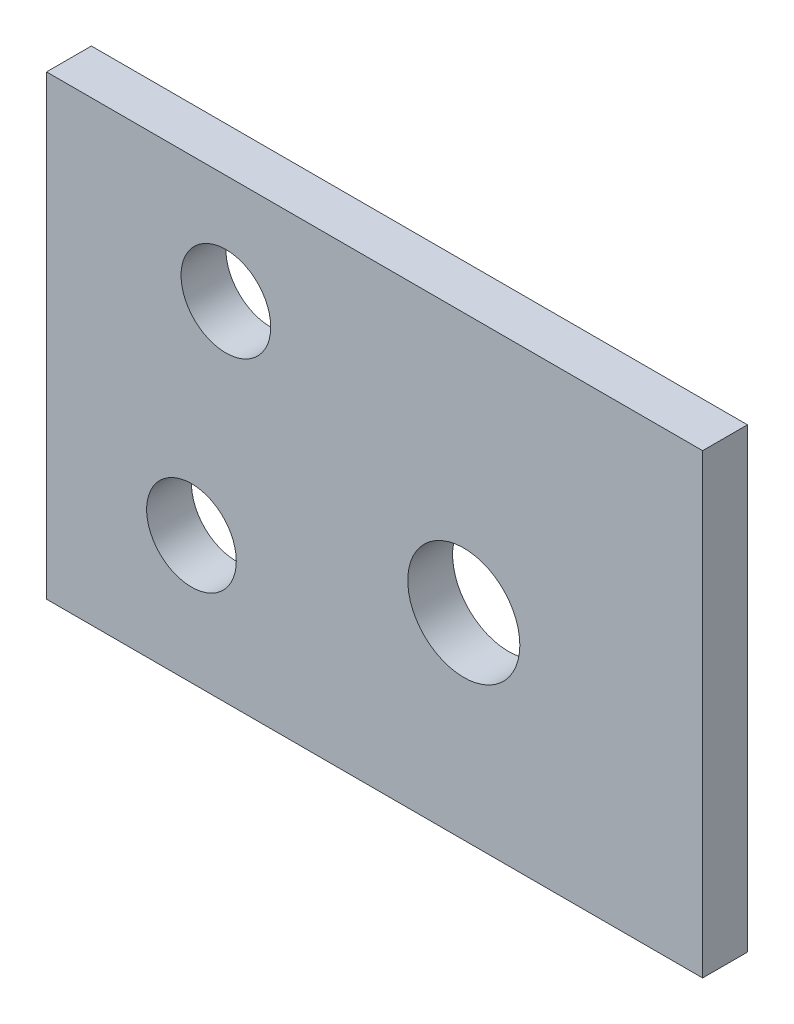
SolidWorks part; units mm, degrees
ref_plane "정면" through (0, 0, 0) normal (0, 0, 1) x (1, 0, 0)
ref_plane "윗면" through (0, 0, 0) normal (0, 1, 0) x (1, 0, 0)
ref_plane "우측면" through (0, 0, 0) normal (1, 0, 0) x (0, 0, -1)
sketch "스케치1" plane through (0, 0, 0) normal (0, 0, 1) x (1, 0, 0)
  line L1 (0, 0) -> (29.2676, 0)
  line L2 (0, 0) -> (0, 20.3729)
  line L3 (0, 20.3729) -> (29.2676, 20.3729)
  line L4 (29.2676, 0) -> (29.2676, 20.3729)
  circle A0 centre (8, 15.5133) radius 2
  circle A1 centre (6.4649, 5.7007) radius 2
  circle A2 centre (18.6139, 8.7847) radius 2.5
  dimension "D1" = 4
  dimension "D2" = 5
  dimension "D3" = 4
  dimension "D4" = 8
extrude "보스-돌출1" add sketch "스케치1" along normal blind 2
